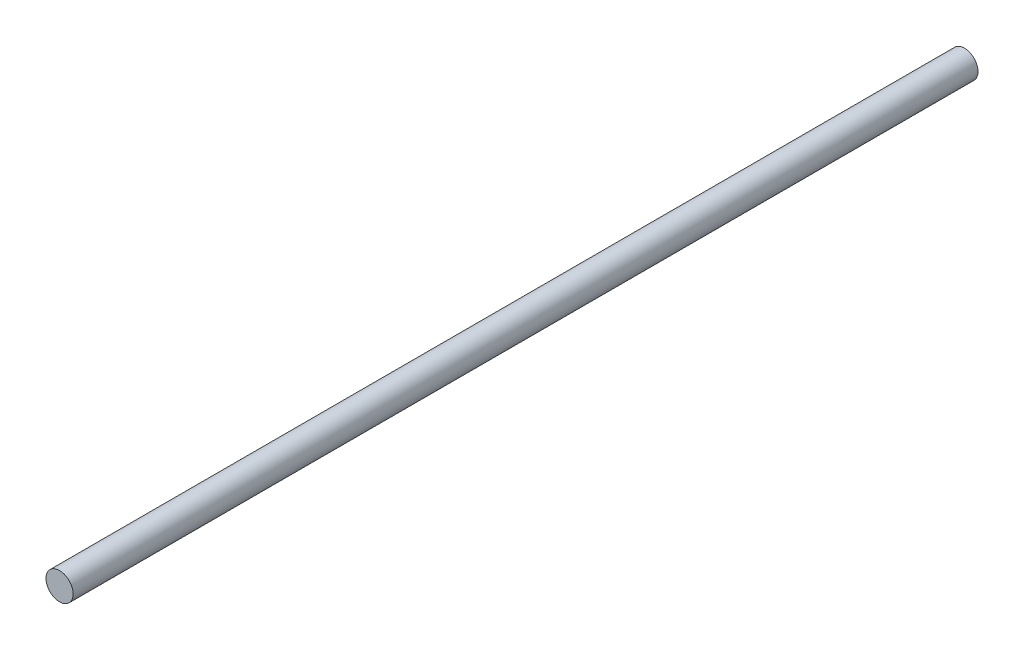
SolidWorks part; units mm, degrees
ref_plane "Спереди" through (0, 0, 0) normal (0, 0, 1) x (1, 0, 0)
ref_plane "Сверху" through (0, 0, 0) normal (0, 1, 0) x (1, 0, 0)
ref_plane "Справа" through (0, 0, 0) normal (1, 0, 0) x (0, 0, -1)
sketch "Эскиз1" plane through (0, 0, 0) normal (0, 0, 1) x (1, 0, 0)
  circle A0 centre (0, 0) radius 1.5
extrude "Вытянуть1" add sketch "Эскиз1" along normal blind 100
